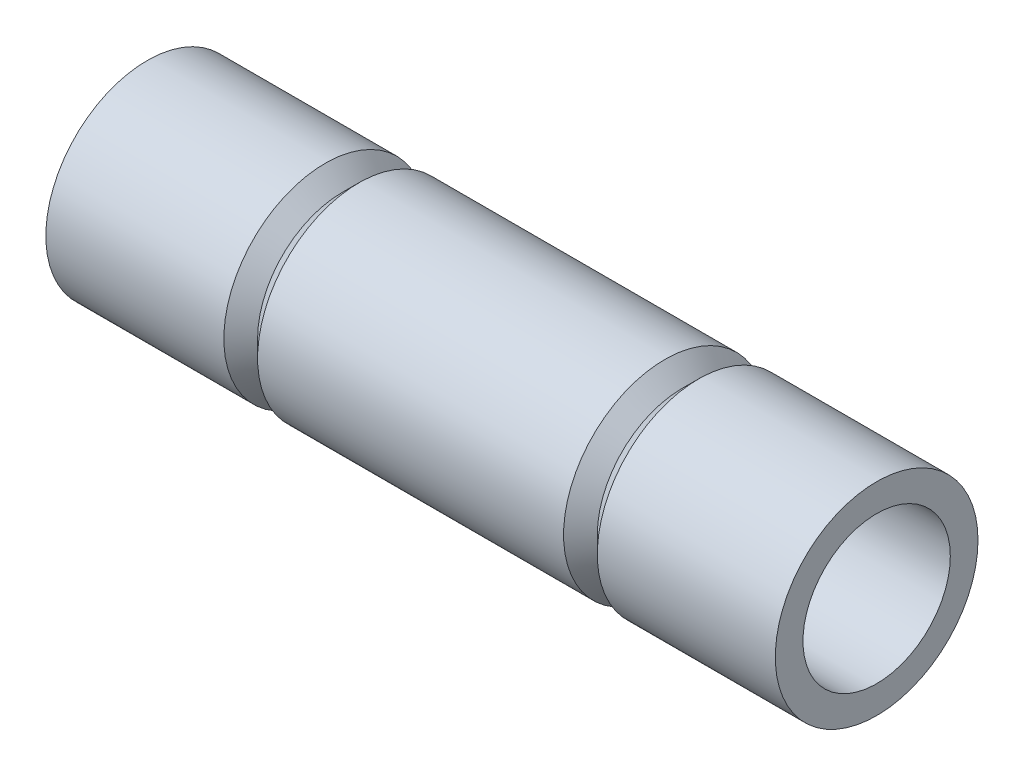
SolidWorks part; units mm, degrees
ref_plane "Front Plane" through (0, 0, 0) normal (0, 0, 1) x (1, 0, 0)
ref_plane "Top Plane" through (0, 0, 0) normal (0, 1, 0) x (1, 0, 0)
ref_plane "Right Plane" through (0, 0, 0) normal (1, 0, 0) x (0, 0, -1)
sketch "Sketch1" plane through (0, 0, 0) normal (0, 1, 0) x (1, 0, 0)
  line L0 (0, 0) -> (-17269.2441, 0) construction
  line L1 (0, 0) -> (0, -15.2908) construction
  line L2 (75.692, -15.2908) -> (-75.692, -15.2908)
  line L3 (-75.692, -15.2908) -> (-75.692, -21.0344)
  line L4 (75.692, -15.2908) -> (75.692, -21.0344)
  line L5 (0, -14.489) -> (0, -21.0344) construction
  line L6 (31.75, -21.0344) -> (-31.75, -21.0344)
  line L7 (-31.75, -21.0344) -> (-35.25, -17.5344)
  line L8 (-35.25, -17.5344) -> (-38.75, -21.0344)
  line L9 (-38.75, -21.0344) -> (-75.692, -21.0344)
  line L10 (31.75, -21.0344) -> (35.25, -17.5344)
  line L11 (35.25, -17.5344) -> (38.75, -21.0344)
  line L12 (38.75, -21.0344) -> (75.692, -21.0344)
  line L13 (-31.75, -21.0344) -> (-38.75, -21.0344) construction
  line L14 (-35.25, -21.0344) -> (-35.25, -17.5344) construction
  line L15 (31.75, -21.0344) -> (38.75, -21.0344) construction
  line L16 (35.25, -17.5344) -> (35.25, -21.0344) construction
  point P8 (0, -15.2908)
  point P15 (0, -21.0344)
  dimension "D1" = 151.384
  dimension "D2" = 15.2908
  dimension "D3" = 5.7436
  dimension "D4" = 63.5
  dimension "D5" = 3.5
revolve "Revolve1" add sketch "Sketch1" angle 360 about L0
